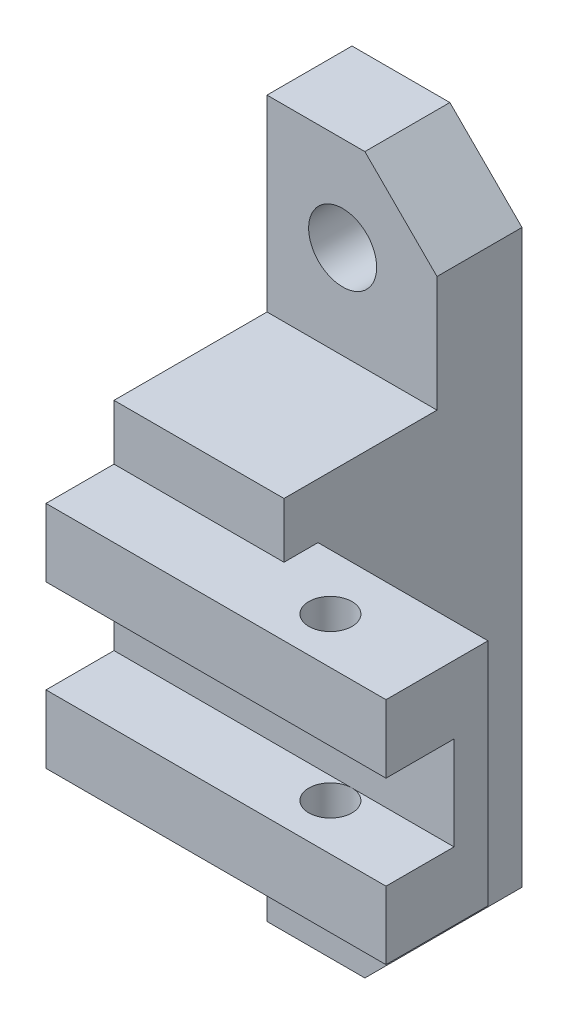
SolidWorks part; units mm, degrees
ref_plane "Front Plane" through (0, 0, 0) normal (0, 0, 1) x (1, 0, 0)
ref_plane "Top Plane" through (0, 0, 0) normal (0, 1, 0) x (1, 0, 0)
ref_plane "Right Plane" through (0, 0, 0) normal (1, 0, 0) x (0, 0, -1)
sketch "Sketch1" plane through (0, 0, 0) normal (0, 0, 1) x (1, 0, 0)
  line L1 (11.05, 21.05) -> (21.05, 21.05)
  line L2 (11.05, 21.05) -> (11.05, -21.05)
  line L3 (11.05, -21.05) -> (21.05, -21.05)
  line L4 (21.05, 21.05) -> (21.05, -21.05)
  line L8 (-16.8074, 21.05) -> (-21.05, 16.8074)
  line L9 (-21.05, 16.8074) -> (-21.05, -16.8074)
  line L10 (-21.05, -16.8074) -> (-16.8074, -21.05)
  line L11 (-16.8074, -21.05) -> (16.8074, -21.05)
  line L12 (16.8074, -21.05) -> (21.05, -16.8074)
  line L13 (21.05, -16.8074) -> (21.05, 16.8074)
  line L14 (21.05, 16.8074) -> (16.8074, 21.05)
  line L15 (16.8074, 21.05) -> (-16.8074, 21.05)
  line L16 (-16.8074, 21.05) -> (-21.05, 16.8074)
  line L17 (-21.05, 16.8074) -> (-21.05, -16.8074)
  line L18 (-21.05, -16.8074) -> (-16.8074, -21.05)
  line L19 (-16.8074, -21.05) -> (16.8074, -21.05)
  line L20 (16.8074, -21.05) -> (21.05, -16.8074)
  line L21 (21.05, -16.8074) -> (21.05, 16.8074)
  line L22 (21.05, 16.8074) -> (16.8074, 21.05)
  line L23 (16.8074, 21.05) -> (-16.8074, 21.05)
  circle A0 centre (15.5, 15.5) radius 2 construction
  circle A1 centre (15.5, -15.5) radius 2 construction
  circle A2 centre (15.5, 15.5) radius 2
  circle A3 centre (15.5, -15.5) radius 2
  dimension "D2" = 10
  dimension "D1" = 0
extrude "Boss-Extrude1" add sketch "Sketch1" along normal blind 5 contours L4 L22 L1 L2 L3 L20 A3 A2
sketch "Sketch2" plane through (0, 0, 5) normal (0, 0, 1) x (1, 0, 0)
  line L0 (21.05, 0) -> (11.05, 0) construction
  line L1 (21.05, 16.8074) -> (21.05, -16.8074) construction
  line L2 (11.05, 21.05) -> (11.05, -21.05) construction
  line L4 (11.05, 10) -> (21.05, 10)
  line L5 (11.05, 10) -> (11.05, -10)
  line L6 (11.05, -10) -> (21.05, -10)
  line L7 (21.05, 10) -> (21.05, -10)
  line L8 (11.05, 10) -> (21.05, -10) construction
  line L9 (11.05, -10) -> (21.05, 10) construction
  point P6 (16.05, 0)
  dimension "D1" = 20
extrude "Boss-Extrude2" add sketch "Sketch2" along normal offset from surface (9 mm away) 10
sketch "Sketch3" plane through (0, 0, 14) normal (0, 0, 1) x (1, 0, 0)
  line L0 (21.05, 0) -> (11.05, 0) construction
  line L1 (21.05, -10) -> (21.05, 10) construction
  line L2 (11.05, 10) -> (11.05, -10) construction
  line L4 (4.9278, 2.75) -> (31.7491, 2.75) construction
  line L5 (4.9278, 2.75) -> (4.9278, -2.75) construction
  line L6 (4.9278, -2.75) -> (31.7491, -2.75) construction
  line L7 (31.7491, 2.75) -> (31.7491, -2.75) construction
  line L8 (4.9278, 2.75) -> (31.7491, -2.75) construction
  line L9 (4.9278, -2.75) -> (31.7491, 2.75) construction
  line L10 (11.05, 2.75) -> (31.05, 2.75)
  line L11 (11.05, 2.75) -> (11.05, 6.75)
  line L12 (11.05, 6.75) -> (31.05, 6.75)
  line L13 (31.05, 2.75) -> (31.05, 6.75)
  line L14 (11.05, -2.75) -> (31.05, -2.75)
  line L15 (11.05, -2.75) -> (11.05, -6.75)
  line L16 (11.05, -6.75) -> (31.05, -6.75)
  line L17 (31.05, -2.75) -> (31.05, -6.75)
  point P6 (18.3385, 0)
  point P11 (11.05, 2.75)
  point P12 (11.05, -2.75)
  dimension "D1" = 5.5
  dimension "D2" = 4
  dimension "D3" = 4
  dimension "D4" = 10
  dimension "D5" = 10
extrude "Boss-Extrude3" add sketch "Sketch3" along normal blind 4
sketch "Sketch4" plane through (0, 0, 14) normal (0, 0, -1) x (-1, 0, 0)
  line L1 (-31.05, -6.75) -> (-21.05, -6.75)
  line L2 (-31.05, -6.75) -> (-31.05, 6.75)
  line L3 (-31.05, 6.75) -> (-21.05, 6.75)
  line L4 (-21.05, -6.75) -> (-21.05, 6.75)
extrude "Boss-Extrude4" add sketch "Sketch4" along normal blind 2
sketch "Sketch5" plane through (0, -6.75, 0) normal (0, -1, 0) x (1, 0, 0)
  line L0 (11.05, 14) -> (21.05, 14) construction
  line L1 (11.05, 14) -> (21.05, 14)
  line L2 (31.05, 18) -> (31.05, 12) construction
  circle A0 centre (25.05, 15.27) radius 1.27
  dimension "D1" = 2.54
  dimension "D2" = 6
extrude "Cut-Extrude1" cut sketch "Sketch5" against normal through all both and the other way through all contours A0
